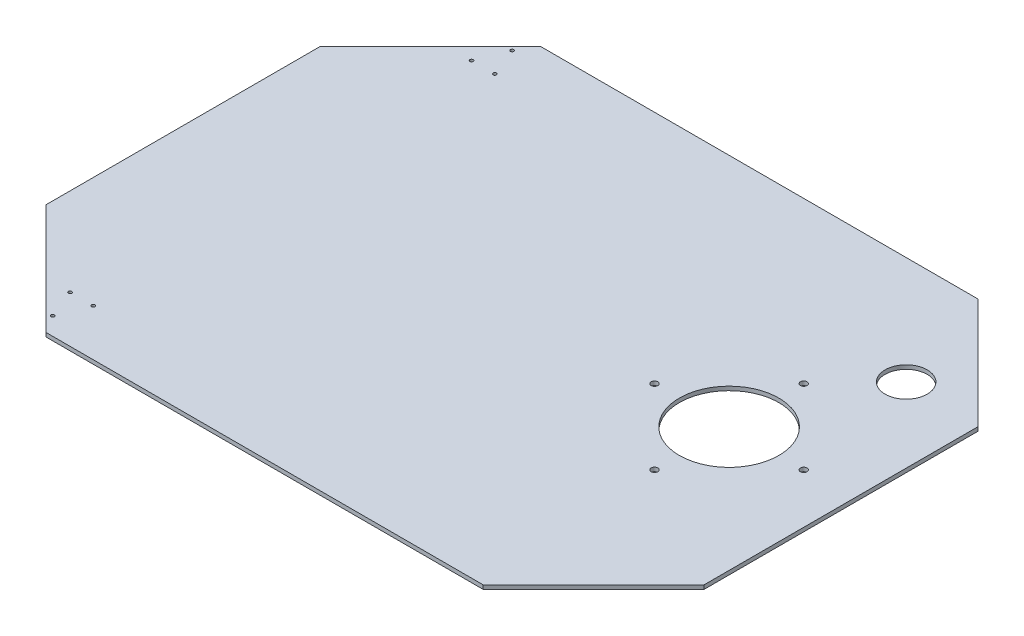
SolidWorks part; units mm, degrees
material "6061 Alloy"
ref_plane "Front Plane" through (0, 0, 0) normal (0, 0, 1) x (1, 0, 0)
ref_plane "Top Plane" through (0, 0, 0) normal (0, 1, 0) x (1, 0, 0)
ref_plane "Right Plane" through (0, 0, 0) normal (1, 0, 0) x (0, 0, -1)
sketch "Sketch1" plane through (0, 0, 0) normal (0, 1, 0) x (1, 0, 0)
  line L1 (-198.4375, 149.225) -> (198.4375, 149.225)
  line L2 (-198.4375, 149.225) -> (-198.4375, -149.225)
  line L3 (-198.4375, -149.225) -> (198.4375, -149.225)
  line L4 (198.4375, 149.225) -> (198.4375, -149.225)
  line L5 (-198.4375, 149.225) -> (198.4375, -149.225) construction
  line L6 (-198.4375, -149.225) -> (198.4375, 149.225) construction
  point P0 (0, 0)
  dimension "D1" = 396.875
  dimension "D2" = 298.45
extrude "Boss-Extrude1" add sketch "Sketch1" along normal blind 2.3813
sketch "Sketch2" plane through (0, 2.3813, 0) normal (0, 1, 0) x (1, 0, 0)
  line L0 (198.4375, -62.164) -> (-198.4375, -62.164) construction
  line L1 (198.4375, -149.225) -> (198.4375, 149.225) construction
  line L2 (-198.4375, 149.225) -> (-198.4375, -149.225) construction
  circle A0 centre (0, 0) radius 4
  text T0 "FUCK YOU, LAURA" font "Clairvaux" height 25.4
  dimension "D1" = 8
extrude "Cut-Extrude1" [suppressed] cut sketch "Sketch2" against normal blind 5
sketch "Sketch3" plane through (0, 2.3813, 0) normal (0, 1, 0) x (1, 0, 0)
  circle A0 centre (0, 0) radius 40 construction
  circle A1 centre (0, 40) radius 2
  circle A2 centre (40, 0) radius 2
  circle A3 centre (0, -40) radius 2
  circle A4 centre (-40, 0) radius 2
  point P14 (0, 0)
  dimension "D1" = 80
  dimension "D2" = 4
  dimension "D3" = 4
extrude "Cut-Extrude2" [suppressed] cut sketch "Sketch3" against normal blind 5
sketch "Sketch4" plane through (0, 2.3813, 0) normal (0, 1, 0) x (1, 0, 0)
  circle A0 centre (45, 45) radius 12.7
  dimension "D3" = 25.4
  dimension "D1" = 45
  dimension "D2" = 45
extrude "Cut-Extrude3" [suppressed] cut sketch "Sketch4" against normal blind 5
sketch "Sketch5" plane through (0, 0, 0) normal (0, -1, 0) x (1, 0, 0)
  line L0 (-138.4375, 149.225) -> (-138.4375, -149.225) construction
  line L1 (-198.4375, 149.225) -> (198.4375, 149.225) construction
  line L2 (198.4375, -149.225) -> (-198.4375, -149.225) construction
  line L3 (-198.4375, -149.225) -> (-198.4375, 149.225) construction
  circle A0 centre (-138.4375, 138.55) radius 1
  circle A1 centre (-138.4375, -138.55) radius 1
  circle A2 centre (-131.4375, -121.05) radius 1
  circle A3 centre (-131.4375, 121.05) radius 1
  circle A4 centre (-145.4375, 121.05) radius 1
  circle A5 centre (-145.4375, -121.05) radius 1
  dimension "D6" = 2
  dimension "D11" = 2
  dimension "D1" = 60
  dimension "D2" = 10.675
  dimension "D3" = 28.175
  dimension "D4" = 7
  dimension "D5" = 7
  dimension "D7" = 10.675
  dimension "D8" = 28.175
  dimension "D9" = 7
  dimension "D10" = 7
extrude "Cut-Extrude4" cut sketch "Sketch5" against normal blind 10
sketch "Sketch6" plane through (0, 2.3813, 0) normal (0, 1, 0) x (1, 0, 0)
  line L0 (198.4375, 149.225) -> (-198.4375, 149.225) construction
  line L2 (198.4375, -149.225) -> (198.4375, 149.225) construction
  circle A0 centre (123.4375, 7.475) radius 45 construction
  circle A1 centre (123.4375, 52.475) radius 2
  circle A2 centre (123.4375, -37.525) radius 2
  circle A3 centre (168.4375, 7.475) radius 2
  circle A4 centre (78.4375, 7.475) radius 2
  circle A5 centre (123.4375, 7.475) radius 30
  dimension "D1" = 90
  dimension "D4" = 4
  dimension "D5" = 60
  dimension "D2" = 75
  dimension "D3" = 141.75
extrude "Cut-Extrude5" cut sketch "Sketch6" against normal blind 10
sketch "Sketch7" plane through (0, 2.3813, 0) normal (0, 1, 0) x (1, 0, 0)
  line L0 (198.4375, 149.225) -> (-198.4375, 149.225) construction
  line L1 (198.4375, -149.225) -> (198.4375, 149.225) construction
  circle A0 centre (153.4375, 84.225) radius 12.7
  dimension "D3" = 25.4
  dimension "D1" = 65
  dimension "D2" = 45
extrude "Cut-Extrude6" cut sketch "Sketch7" against normal blind 10
sketch "Sketch8" plane through (0, 2.3813, 0) normal (0, 1, 0) x (1, 0, 0)
  line L0 (131.7625, -149.225) -> (198.4375, -82.55)
  line L1 (-198.4375, -149.225) -> (198.4375, -149.225) construction
  line L2 (198.4375, -149.225) -> (198.4375, 149.225) construction
  line L3 (198.4375, -82.55) -> (198.4375, -149.225)
  line L4 (198.4375, -149.225) -> (131.7625, -149.225)
  line L5 (198.4375, 149.225) -> (131.7625, 149.225)
  line L6 (198.4375, 149.225) -> (-198.4375, 149.225) construction
  line L7 (131.7625, 149.225) -> (198.4375, 82.55)
  line L8 (198.4375, 82.55) -> (198.4375, 149.225)
  dimension "D1" = 45
  dimension "D2" = 45
  dimension "D3" = 165.1
  dimension "D4" = 82.55
extrude "Cut-Extrude7" cut sketch "Sketch8" against normal blind 10
mirror "Mirror1" about plane through (0, 0, 0) normal (1, 0, 0) of "Cut-Extrude7"
equation "\"D3@Sketch8\"=6.5in"
equation "\"D4@Sketch8\"=3.25in"
equation "\"D2@Sketch1\"=11.75in"
equation "\"D1@Sketch1\"=15.625in"
equation "\"D1@Boss-Extrude1\"=3/32"
